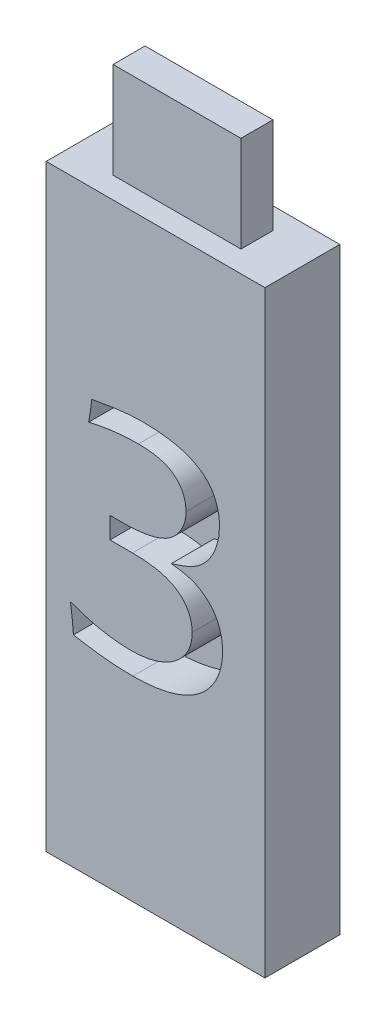
SolidWorks part; units mm, degrees
ref_plane "Front Plane" through (0, 0, 0) normal (0, 0, 1) x (1, 0, 0)
ref_plane "Top Plane" through (0, 0, 0) normal (0, 1, 0) x (1, 0, 0)
ref_plane "Right Plane" through (0, 0, 0) normal (1, 0, 0) x (0, 0, -1)
sketch "Sketch1" plane through (0, 0, 0) normal (0, 0, 1) x (1, 0, 0)
  line L1 (-8.69, -23.749) -> (8.69, -23.749)
  line L2 (-8.69, -23.749) -> (-8.69, 23.749)
  line L3 (-8.69, 23.749) -> (8.69, 23.749)
  line L4 (8.69, -23.749) -> (8.69, 23.749)
  line L5 (-8.69, -23.749) -> (8.69, 23.749) construction
  line L6 (-8.69, 23.749) -> (8.69, -23.749) construction
  point P0 (0, 0)
  dimension "D1" = 17.38
  dimension "D2" = 47.498
extrude "Boss-Extrude1" add sketch "Sketch1" along normal blind 5.95
sketch "Sketch2" plane through (0, 0, 5.95) normal (0, 0, 1) x (1, 0, 0)
  line L0 (0, 23.749) -> (0, -23.749) construction
  line L1 (8.69, 23.749) -> (-8.69, 23.749) construction
  line L2 (-8.69, -23.749) -> (8.69, -23.749) construction
  line L3 (0, -23.749) -> (0, 0) construction
  line L4 (0, 0) -> (-8.69, 0) construction
  line L5 (-8.69, 23.749) -> (-8.69, -23.749) construction
  line L6 (-8.69, 0) -> (8.69, 0) construction
  line L7 (8.69, -23.749) -> (8.69, 23.749) construction
  line L8 (-8.69, -23.749) -> (8.69, -23.749) construction
  line L9 (-8.69, -21.209) -> (8.69, -21.209) construction
  line L10 (-8.69, -18.669) -> (8.69, -18.669) construction
  line L11 (-8.69, -16.129) -> (8.69, -16.129) construction
  line L12 (-8.69, -13.589) -> (8.69, -13.589) construction
  line L13 (-8.69, -11.049) -> (8.69, -11.049) construction
  line L14 (-8.69, -8.509) -> (8.69, -8.509) construction
  line L15 (-8.69, -5.969) -> (8.69, -5.969) construction
  line L16 (-8.69, -3.429) -> (8.69, -3.429) construction
  line L17 (-8.69, -0.889) -> (8.69, -0.889) construction
  line L18 (-8.69, 1.651) -> (8.69, 1.651) construction
  line L19 (-8.69, 4.191) -> (8.69, 4.191) construction
  line L20 (-8.69, 6.731) -> (8.69, 6.731) construction
  line L21 (-8.69, 9.271) -> (8.69, 9.271) construction
  line L22 (-8.69, 11.811) -> (8.69, 11.811) construction
  line L23 (-8.69, 14.351) -> (8.69, 14.351) construction
  line L24 (-8.69, 16.891) -> (8.69, 16.891) construction
  line L25 (-8.69, 19.431) -> (8.69, 19.431) construction
  line L26 (-8.69, 21.971) -> (8.69, 21.971) construction
  line L27 (-8.69, 23.749) -> (-8.69, -23.749) construction
  line L28 (-6.15, 23.749) -> (-6.15, -23.749) construction
  line L29 (-3.61, 23.749) -> (-3.61, -23.749) construction
  line L30 (-1.07, 23.749) -> (-1.07, -23.749) construction
  line L31 (1.47, 23.749) -> (1.47, -23.749) construction
  line L32 (4.01, 23.749) -> (4.01, -23.749) construction
  line L33 (6.55, 23.749) -> (6.55, -23.749) construction
  text T0 "3\r\n\r\n\r\n" font "Eras Medium ITC" height in points 72
  dimension "D1" = 19
  dimension "D2" = 2.54
  dimension "D4" = 2.54
  dimension "D3" = 7
extrude "Cut-Extrude1" cut sketch "Sketch2" against normal blind 3.41
sketch "Sketch3" plane through (0, 23.749, 0) normal (0, 1, 0) x (1, 0, 0)
  line L0 (0, 0) -> (0, -5.95) construction
  line L1 (8.69, -5.95) -> (-8.69, -5.95) construction
  line L2 (0, -5.95) -> (0, -2.975) construction
  line L3 (0, -2.975) -> (-8.69, -2.975) construction
  line L4 (-8.69, -5.95) -> (-8.69, 0) construction
  line L5 (-8.69, -2.975) -> (8.69, -2.975) construction
  line L6 (8.69, -5.95) -> (8.69, 0) construction
  line L8 (-5.08, -4.245) -> (5.08, -4.245)
  line L9 (-5.08, -4.245) -> (-5.08, -1.705)
  line L10 (-5.08, -1.705) -> (5.08, -1.705)
  line L11 (5.08, -4.245) -> (5.08, -1.705)
  line L12 (-5.08, -4.245) -> (5.08, -1.705) construction
  line L13 (-5.08, -1.705) -> (5.08, -4.245) construction
  dimension "D1" = 2.54
  dimension "D2" = 10.16
extrude "Boss-Extrude2" add sketch "Sketch3" along normal blind 7.62
